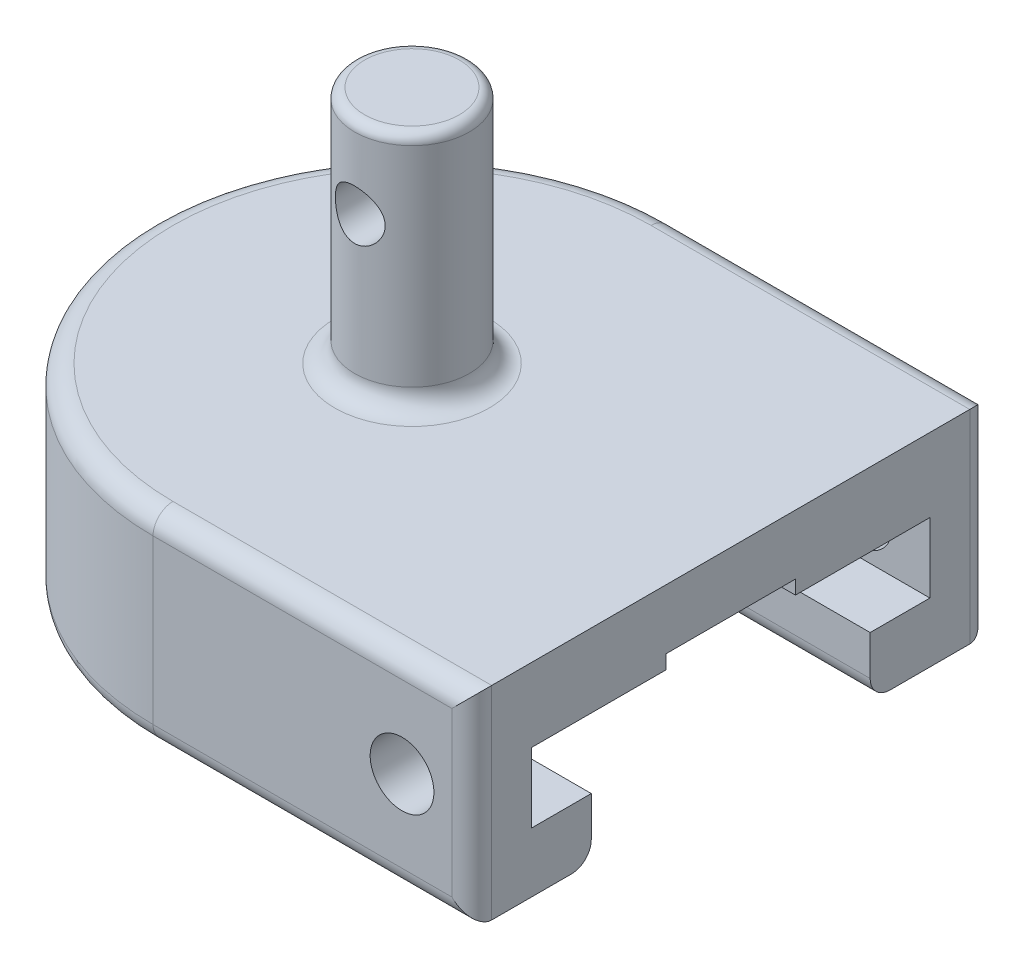
SolidWorks part; units mm, degrees
ref_plane "Front Plane" through (0, 0, 0) normal (0, 0, 1) x (1, 0, 0)
ref_plane "Top Plane" through (0, 0, 0) normal (0, 1, 0) x (1, 0, 0)
ref_plane "Right Plane" through (0, 0, 0) normal (1, 0, 0) x (0, 0, -1)
sketch "Sketch1" plane through (0, 0, 0) normal (0, 1, 0) x (1, 0, 0)
  line L0 (0, 13) -> (16, 13)
  line L1 (0, -13) -> (16, -13)
  line L2 (0, 7) -> (16, 7)
  line L3 (16, 13) -> (16, 7)
  line L4 (0, -7) -> (16, -7)
  line L5 (16, -7) -> (16, -13)
  arc A0 (0, 7) -> (0, -7) centre (0, 0) ccw
  arc A1 (0, 13) -> (0, -13) centre (0, 0) ccw
  dimension "D1" = 6
  dimension "D2" = 7
  dimension "D3" = 16
  dimension "D4" = 16
extrude "Boss-Extrude1" add sketch "Sketch1" along normal blind 3
sketch "Sketch2" plane through (0, 3, 0) normal (0, 1, 0) x (1, 0, 0)
  line L0 (0, 13) -> (16, 13)
  line L1 (16, 13) -> (16, 10)
  line L2 (16, 7) -> (16, 13) construction
  line L3 (16, -13) -> (0, -13)
  line L4 (16, -13) -> (16, -10)
  line L7 (16, -13) -> (16, -7) construction
  line L8 (0, 10) -> (16, 10)
  line L9 (0, -10) -> (16, -10)
  arc A0 (0, 10) -> (0, -10) centre (0, 0) ccw
  arc A1 (0, 13) -> (0, -13) centre (0, 0) ccw
  dimension "D2" = 3
extrude "Boss-Extrude2" add sketch "Sketch2" along normal blind 3.5
sketch "Sketch3" plane through (0, 6.5, 0) normal (0, 1, 0) x (1, 0, 0)
  line L0 (16, 13) -> (0, 13)
  line L1 (16, 13) -> (16, 7)
  line L3 (0, -13) -> (16, -13)
  line L4 (16, -13) -> (16, -7)
  line L5 (16, -7) -> (0, -7) construction
  line L6 (16, -10) -> (16, -7) construction
  line L8 (16, 7) -> (16, -7)
  arc A1 (0, 13) -> (0, -13) centre (0, 0) ccw
extrude "Boss-Extrude3" add sketch "Sketch3" along normal blind 3.7
sketch "Sketch4" plane through (0, 10.2, 0) normal (0, 1, 0) x (1, 0, 0)
  circle A0 centre (0, 0) radius 2.88
  dimension "D1" = 5.76
extrude "Boss-Extrude4" add sketch "Sketch4" along normal blind 12
sketch "Sketch9" plane through (16, 0, 0) normal (1, 0, 0) x (0, 0, -1)
  line L0 (-10, 6.5) -> (10, 6.5) construction
  line L1 (-3.25, 6.5) -> (3.25, 6.5)
  line L2 (-3.25, 6.5) -> (-3.25, 7.2)
  line L3 (-3.25, 7.2) -> (3.25, 7.2)
  line L4 (3.25, 6.5) -> (3.25, 7.2)
  line L5 (0, 10.2) -> (0, 6.5) construction
  line L6 (-13, 10.2) -> (13, 10.2) construction
  line L7 (-10, 6.5) -> (10, 6.5) construction
  line L8 (0, 7.2) -> (0, 6.5) construction
  dimension "D1" = 6.5
  dimension "D2" = 0.7
extrude "Cut-Extrude2" cut sketch "Sketch9" against normal blind 23
hole_wizard "Ø2.5mm Dowel Hole1" positions "3DSketch4" profile "Sketch7" hole size "Ø2.5" standard "ANSI Metric" end condition through all
sketch3d "3DSketch4"
  point P0 (-0.0024, 18.1049, 2.88)
  point P12 (-0.0024, 18.1049, 2.88)
sketch "Sketch7" plane through (-0.0024, 18.1049, 2.88) normal (0, 1, 0) x (1, 0, 0.0008)
  line L0 (0, 0) -> (0, 15.8935)
  line L1 (0, 15.8935) -> (1.25, 15.8935)
  line L2 (1.25, 15.8935) -> (1.25, 0)
  line L5 (1.25, 0) -> (0, 0)
  line L11 (0, -6.35) -> (0, 107.95) construction
  dimension "Thru Hole Dia." = 2.5
  dimension "Thru Hole Depth" = 15.8935
sketch "Sketch8" plane through (0, 0, 13) normal (0, 0, 1) x (1, 0, 0)
  line L0 (16, 5.1) -> (0, 5.1) construction
  line L1 (16, 10.2) -> (16, 0) construction
  line L2 (0, 10.2) -> (0, 0) construction
  circle A0 centre (12.5, 5.1) radius 1.6
  dimension "D1" = 3.2
  dimension "D2" = 3.5
extrude "Cut-Extrude1" cut sketch "Sketch8" against normal through all
fillet "Fillet1" radius 1 11 edges at (8, 10.2, -13) (-13, 10.2, 0) (8, 0, -13) (-13, 0, 0) (8, 10.2, 13) (16, 5.1, 13) (8, 0, 13) (8, 0, -7) (-7, 0, 0) (8, 0, 7) (16, 5.1, -13)
fillet "Fillet2" radius 1 1 edges at (0, 10.2, 2.88)
fillet "Fillet3" radius 0.5 1 edges at (0, 22.2, 2.88)
